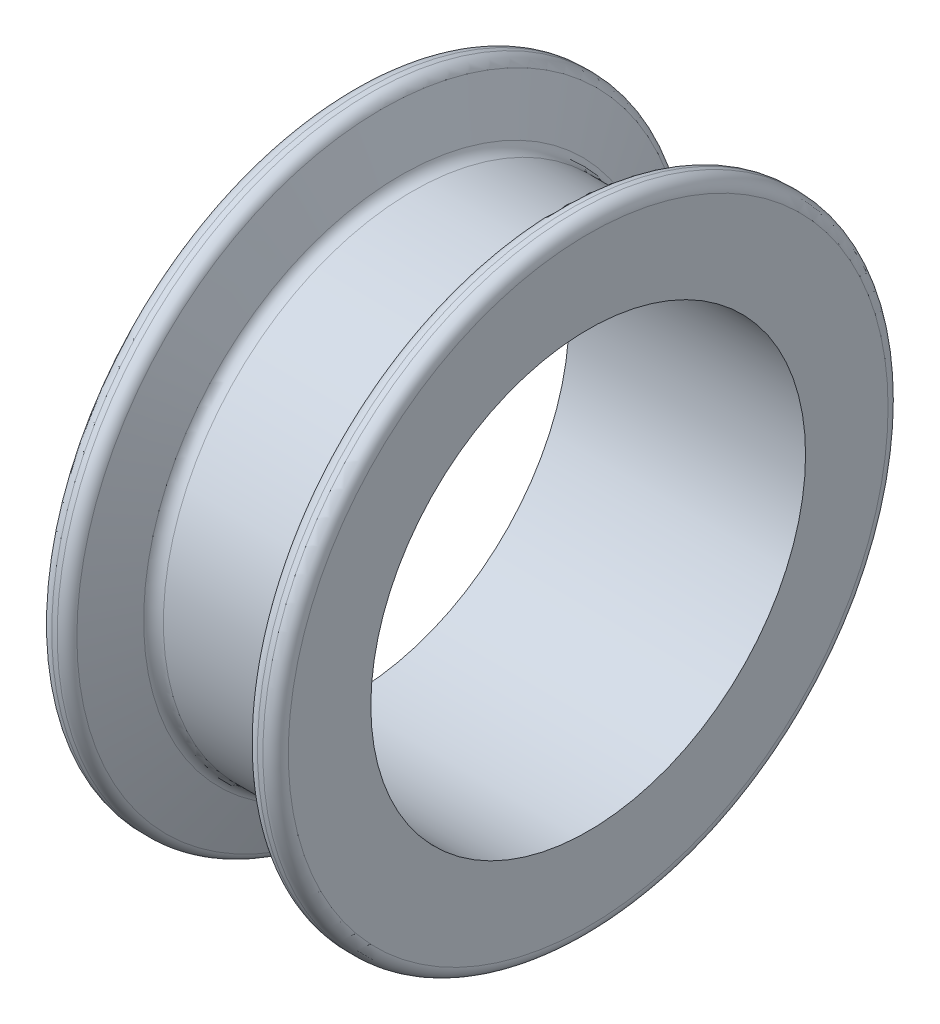
SolidWorks part; units mm, degrees
ref_plane "Front Plane" through (0, 0, 0) normal (0, 0, 1) x (1, 0, 0)
ref_plane "Top Plane" through (0, 0, 0) normal (0, 1, 0) x (1, 0, 0)
ref_plane "Right Plane" through (0, 0, 0) normal (1, 0, 0) x (0, 0, -1)
sketch "Sketch1" plane through (0, 0, 0) normal (0, 0, 1) x (1, 0, 0)
  line L1 (215.5697, -120.5319) -> (223.0242, -120.5319)
  line L2 (223.0242, -120.5319) -> (223.0242, -123.1319)
  line L3 (222.6242, -123.5319) -> (222.4535, -123.5319)
  line L4 (222.0826, -123.2817) -> (221.4772, -121.7822)
  line L5 (219.297, -120.5319) -> (219.297, -120.9081) construction
  line L6 (221.1062, -121.5319) -> (217.4877, -121.5319)
  line L7 (215.5697, -120.5319) -> (215.5697, -123.1319)
  line L8 (216.5114, -123.2817) -> (217.1168, -121.7822)
  line L9 (215.9697, -123.5319) -> (216.1405, -123.5319)
  line L11 (220.435, -113.6819) -> (219.3883, -113.6819) construction
  arc A0 (215.5697, -123.1319) -> (215.9697, -123.5319) centre (215.9697, -123.1319) ccw
  arc A1 (216.5114, -123.2817) -> (216.1405, -123.5319) centre (216.1405, -123.1319) cw
  arc A2 (217.1168, -121.7822) -> (217.4877, -121.5319) centre (217.4877, -121.9319) cw
  arc A3 (221.4772, -121.7822) -> (221.1062, -121.5319) centre (221.1062, -121.9319) ccw
  arc A4 (223.0242, -123.1319) -> (222.6242, -123.5319) centre (222.6242, -123.1319) cw
  arc A5 (222.4535, -123.5319) -> (222.0826, -123.2817) centre (222.4535, -123.1319) cw
  point P10 (219.297, -121.5319)
  point P14 (215.5697, -123.5319)
  point P17 (216.4103, -123.5319)
  point P20 (217.2178, -121.5319)
  point P23 (221.3761, -121.5319)
  point P26 (223.0242, -123.5319)
  point P29 (222.1836, -123.5319)
  point P30 (219.6436, -121.5319)
  point P31 (218.03, -123.2817)
  dimension "D3" = 0.4
  dimension "D1" = 3
  dimension "D2" = 1
revolve "Revolve1" add sketch "Sketch1" angle 360 about L11
ref_plane "Plane1" through (219.297, 0, 0) normal (1, 0, 0) x (0, 0, -1)
sketch "Sketch2" plane through (219.297, 0, 0) normal (1, 0, 0) x (0, 0, -1)
  circle A0 centre (0, -113.6819) radius 4.5636
ref_point "Point1"
